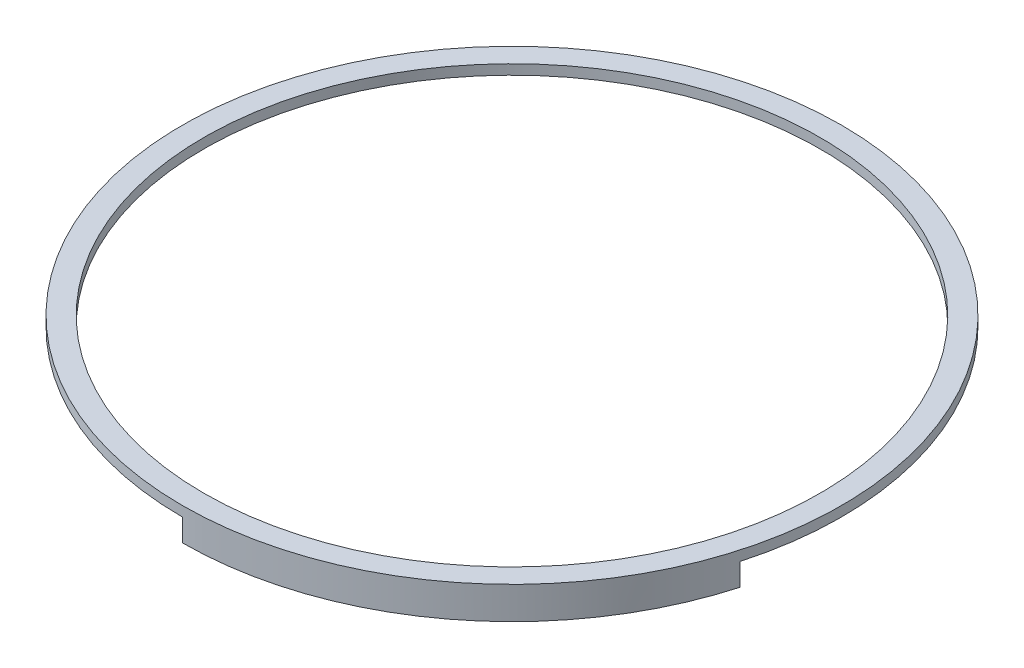
SolidWorks part; units mm, degrees
ref_plane "Front Plane" through (0, 0, 0) normal (0, 0, 1) x (1, 0, 0)
ref_plane "Top Plane" through (0, 0, 0) normal (0, 1, 0) x (1, 0, 0)
ref_plane "Right Plane" through (0, 0, 0) normal (1, 0, 0) x (0, 0, -1)
sketch "Sketch2" plane through (0, 0, 0) normal (0, 1, 0) x (1, 0, 0)
  circle A0 centre (0, 0) radius 62
  circle A1 centre (0, 0) radius 66.3
  dimension "D1" = 124
  dimension "D2" = 132.6
extrude "Boss-Extrude1" add sketch "Sketch2" along normal blind 2
sketch "Sketch3" plane through (0, 0, 0) normal (0, -1, 0) x (1, 0, 0)
  line L0 (0, 0) -> (0, 66.3) construction
  line L1 (63.8328, 17.9182) -> (62.87, 17.6479)
  line L2 (0, 65.3) -> (0, 66.3)
  circle A0 centre (0, 0) radius 65.3
  circle A2 centre (0, 0) radius 66.3 construction
  circle A3 centre (0, 0) radius 66.3
  arc A4 (0, 66.3) -> (63.8328, 17.9182) centre (0, 0) cw
  circle M1 centre (0, 0) radius 66.3
  dimension "D1" = 1
  dimension "D2" = 86
extrude "Boss-Extrude2" add sketch "Sketch3" along normal blind 4.5 contours A0 L1 L2 M1
